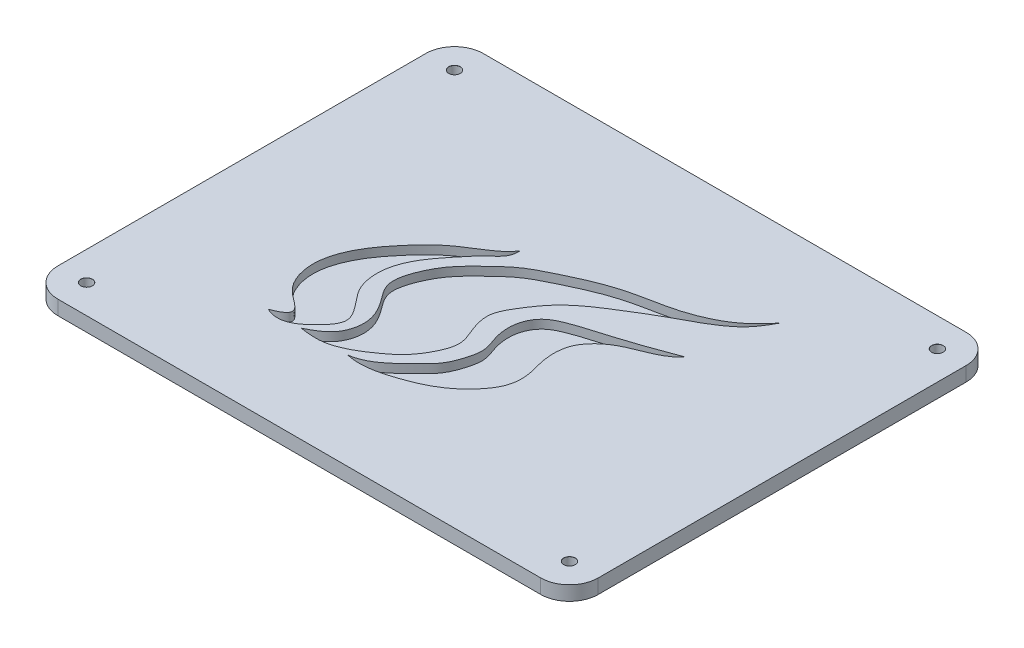
SolidWorks part; units mm, degrees
ref_plane "Plano frontal" through (0, 0, 0) normal (0, 0, 1) x (1, 0, 0)
ref_plane "Plano superior" through (0, 0, 0) normal (0, 1, 0) x (1, 0, 0)
ref_plane "Plano direito" through (0, 0, 0) normal (1, 0, 0) x (0, 0, -1)
ref_plane "Plano1" through (0, -5, 0) normal (0, -1, 0) x (1, 0, 0)
sketch "Esboço1" plane through (0, -5, 0) normal (0, -1, 0) x (1, 0, 0)
  line L0 (0, -148) -> (188, -148)
  line L1 (188, -148) -> (188, 0)
  line L2 (188, 0) -> (0, 0)
  line L3 (0, 0) -> (0, -148)
extrude "Ressalto-extrusão1" add sketch "Esboço1" against normal blind 5
sketch "Esboço2" plane through (0, -5, 0) normal (0, -1, 0) x (1, 0, 0)
  line L0 (5, -5) -> (183, -5)
  line L1 (183, -5) -> (183, -143)
  line L2 (183, -143) -> (5, -143)
  line L3 (5, -143) -> (5, -5)
extrude "Ressalto-extrusão2" add sketch "Esboço2" along normal blind 5
sketch "Esboço3" plane through (0, 0, 0) normal (0, 1, 0) x (-1, 0, 0)
  spline S0 degree 3 poles (-75.8513, -94.906) (-72.8535, -90.4619) (-63.519, -86.5735) (-53.3882, -76.0624) (-46.2023, -66.6508) (-42.9339, -55.6874) (-44.8426, -47.1017) (-50.6606, -40.2907) (-58.6418, -36.77) (-49.6316, -33.5768) knots 0 0 0 0 0.221731 0.361071 0.538534 0.656522 0.776882 0.841137 1 1 1 1
  spline S1 degree 3 poles (-49.6316, -33.5768) (-55.1932, -30.8638) (-61.3839, -35.1823) (-67.8569, -43.2627) (-64.0282, -49.8709) (-58.1961, -55.5638) (-57.0305, -66.1333) (-61.21, -75.4924) (-66.5475, -81.8637) (-71.7761, -88.296) (-76.1964, -90.9559) (-75.8513, -94.906) knots 0 0 0 0 0.190021 0.27318 0.335509 0.44453 0.578502 0.692991 0.817664 0.88529 1 1 1 1
extrude "Corte-extrusão1" cut sketch "Esboço3" against normal blind 3
sketch "Esboço4" plane through (0, 0, 0) normal (0, 1, 0) x (-1, 0, 0)
  spline S0 degree 3 poles (-136.7297, -91.7327) (-130.548, -89.419) (-121.9958, -86.2855) (-111.4177, -83.31) (-105.4901, -81.3156) (-100.2096, -78.9101) (-97.1664, -73.8232) (-96.8303, -68.8944) (-97.7553, -63.9422) (-99.9783, -59.2599) (-98.6794, -53.2404) (-96.4396, -47.1702) (-88.7973, -40.1703) (-83.295, -34.4435) (-77.2093, -33.5768) knots 0 0 0 0 0.208187 0.287593 0.345987 0.406774 0.465273 0.52264 0.558971 0.624214 0.679619 0.74702 0.825667 1 1 1 1
  spline S1 degree 3 poles (-77.2093, -33.5768) (-82.5851, -32.319) (-91.3527, -34.4282) (-101.3989, -38.5316) (-107.5302, -43.0726) (-111.3527, -47.2007) (-114.2478, -51.9233) (-114.9383, -56.8005) (-114.1515, -61.4169) (-112.8663, -65.5978) (-112.4174, -70.2105) (-113.0072, -74.7648) (-115.8896, -79.4687) (-123.6948, -85.6994) (-132.4436, -86.9091) (-136.7297, -91.7327) knots 0 0 0 0 0.166387 0.277066 0.33674 0.403034 0.451941 0.507331 0.552146 0.597486 0.643567 0.696221 0.737301 0.812803 1 1 1 1
extrude "Corte-extrusão2" cut sketch "Esboço4" against normal blind 3
ref_plane "Plano2" through (0, -9, 0) normal (0, 1, 0) x (1, 0, 0)
sketch "Esboço5" plane through (0, -9, 0) normal (0, 1, 0) x (1, 0, 0)
  spline S0 degree 3 poles (142.7977, 118.3188) (141.5574, 116.1036) (139.133, 111.7737) (133.2828, 107.1268) (127.0167, 103.5038) (120.5507, 100.1522) (114.3105, 96.3948) (108.1243, 92.5597) (102.0741, 88.4936) (96.7829, 83.3592) (92.8219, 77.3269) (88.9832, 70.7249) (90.8449, 63.3932) (94.2742, 56.7643) (91.4301, 49.5234) (87.454, 43.4921) (81.5905, 38.9932) (75.492, 35.0818) (68.3981, 32.6003) (63.5148, 33.2504) (61.0626, 33.5768) knots 0 0 0 0 0.057637 0.112657 0.168143 0.223818 0.279375 0.335006 0.390602 0.4463 0.501841 0.557867 0.611847 0.66681 0.721725 0.777322 0.832941 0.888514 0.944017 1 1 1 1
  spline S1 degree 3 poles (61.0626, 33.5768) (63.7068, 34.9359) (68.9279, 37.6195) (71.5706, 46.8653) (67.9201, 54.8174) (61.573, 61.5577) (64.0816, 70.7817) (68.2137, 78.2638) (74.4803, 84.3186) (80.7865, 90.2357) (88.5732, 94.0884) (96.3256, 97.7809) (104.4036, 100.8664) (112.8289, 102.6904) (121.3013, 104.2953) (129.403, 107.2855) (136.9905, 111.7221) (140.847, 116.1029) (142.7977, 118.3188) knots 0 0 0 0 0.062549 0.123506 0.186161 0.247751 0.310956 0.373508 0.436067 0.498651 0.561042 0.623646 0.68612 0.748656 0.811154 0.873632 0.93608 1 1 1 1
extrude "Corte-extrusão3" cut sketch "Esboço5" against normal blind 3 from surface
hole_wizard "Furo de diâmetro Ø4.0 (4)1" positions "Esboço7" profile "Esboço6" hole size "Ø4.0" standard "Ansi Metric"
sketch "Esboço7" plane through (0, 0, 0) normal (0, 1, 0) x (1, 0, 0)
  point P0 (178, 138)
  point P1 (178, 10)
  point P2 (10, 10)
  point P3 (10, 138)
sketch "Esboço6" plane through (178, 0, -138) normal (1, 0, 0) x (0, 0, 1)
  line L0 (0, 0) -> (0, 10)
  line L1 (0, 10) -> (2, 10)
  line L2 (2, 10) -> (2, 0)
  line L5 (2, 0) -> (0, 0)
  line L11 (0, -6.35) -> (0, 107.95) construction
  dimension "Thru Hole Dia." = 4
  dimension "Thru Hole Depth" = 10
chamfer "Chanfro1" distance 0.025 angle 45 4 edges at (10, 0, -136) (10, 0, -8) (178, 0, -8) (178, 0, -136)
fillet "Filete1" radius 10 8 edges at (0, -2.5, -148) (188, -2.5, 0) (188, -2.5, -148) (5, -7.5, -143) (0, -2.5, 0) (183, -7.5, -5) (5, -7.5, -5) (183, -7.5, -143)
